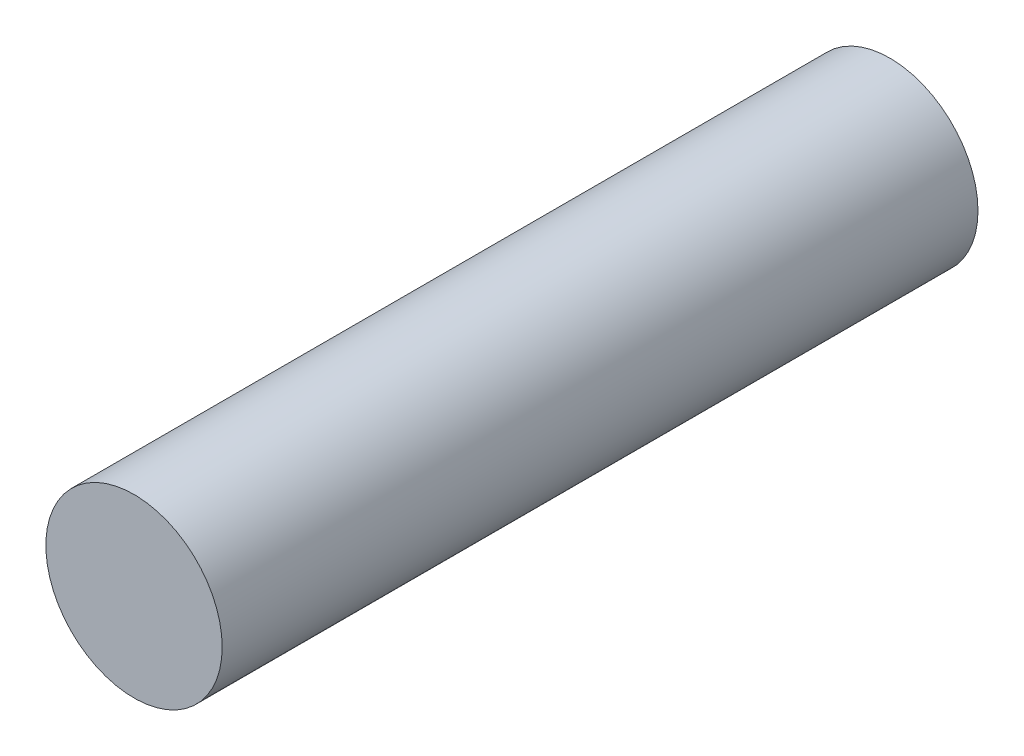
SolidWorks part; units mm, degrees
ref_plane "Front Plane" through (0, 0, 0) normal (0, 0, 1) x (1, 0, 0)
ref_plane "Top Plane" through (0, 0, 0) normal (0, 1, 0) x (1, 0, 0)
ref_plane "Right Plane" through (0, 0, 0) normal (1, 0, 0) x (0, 0, -1)
sketch "Sketch1" plane through (0, 0, 0) normal (0, 0, 1) x (1, 0, 0)
  circle A0 centre (0, 0) radius 1.75
  dimension "D1" = 3.5
extrude "Boss-Extrude1" add sketch "Sketch1" along normal blind 15
